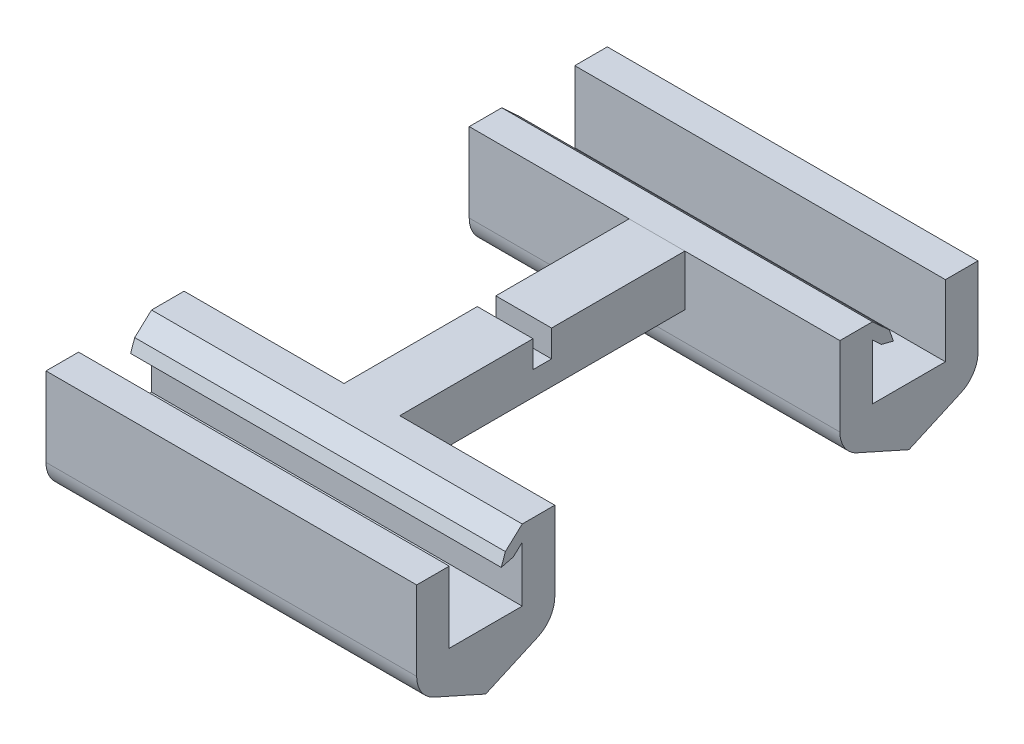
SolidWorks part; units mm, degrees
ref_plane "Front Plane" through (0, 0, 0) normal (0, 0, 1) x (1, 0, 0)
ref_plane "Top Plane" through (0, 0, 0) normal (0, 1, 0) x (1, 0, 0)
ref_plane "Right Plane" through (0, 0, 0) normal (1, 0, 0) x (0, 0, -1)
sketch "Sketch1" plane through (0, 0, 0) normal (1, 0, 0) x (0, 0, -1)
  line L0 (0, 0) -> (0, 50000) construction
  line L1 (6, -0.5435) -> (6, 0) construction
  line L2 (6.717, -0.9314) -> (6.4415, -0.6779) construction
  line L3 (6.5769, -0.5307) -> (6.3061, -0.8251) construction
  line L4 (6.3061, -0.8251) -> (6, -0.5435)
  line L5 (6.717, -0.9314) -> (6.3061, -0.8251)
  line L6 (6.5769, -0.5307) -> (6.717, -0.9314)
  line L7 (6, 0) -> (6.5769, -0.5307)
  line L8 (4.8841, 0) -> (4.8841, -2.7135)
  line L9 (5.4755, -3.6262) -> (7.25, -4.4206)
  line L10 (7.25, -1.3683) -> (7.25, 49998.6317) construction
  line L11 (-7.25, -1.3683) -> (-7.25, 49998.6317) construction
  line L12 (-6, 0) -> (-4.8841, 0)
  line L13 (-6, -2.4374) -> (-6, -0.5435)
  line L14 (-8.5, -2.4374) -> (-6, -2.4374)
  line L15 (-9.0245, -3.6262) -> (-7.25, -4.4206)
  line L16 (-9.6159, 0) -> (-9.6159, -2.7135)
  line L17 (-8.5, -2.4374) -> (-8.5, 0)
  line L18 (-8.5, 0) -> (-9.6159, 0)
  line L19 (-5.4755, -3.6262) -> (-7.25, -4.4206)
  line L20 (-4.8841, 0) -> (-4.8841, -2.7135)
  line L21 (-6, 0) -> (-6.5769, -0.5307)
  line L22 (-6.5769, -0.5307) -> (-6.717, -0.9314)
  line L23 (-6.717, -0.9314) -> (-6.3061, -0.8251)
  line L24 (-6.3061, -0.8251) -> (-6, -0.5435)
  line L25 (-6.5769, -0.5307) -> (-6.3061, -0.8251) construction
  line L26 (-6.717, -0.9314) -> (-6.4415, -0.6779) construction
  line L27 (-6, -0.5435) -> (-6, 0) construction
  line L28 (8.5, 0) -> (9.6159, 0)
  line L29 (8.5, -2.4374) -> (8.5, 0)
  line L30 (9.6159, 0) -> (9.6159, -2.7135)
  line L31 (9.0245, -3.6262) -> (7.25, -4.4206)
  line L32 (8.5, -2.4374) -> (6, -2.4374)
  line L33 (6, -2.4374) -> (6, -0.5435)
  line L34 (6, 0) -> (4.8841, 0)
  arc A0 (-5.4755, -3.6262) -> (-4.8841, -2.7135) centre (-5.8841, -2.7135) ccw
  arc A1 (-9.0245, -3.6262) -> (-9.6159, -2.7135) centre (-8.6159, -2.7135) cw
  arc A2 (9.0245, -3.6262) -> (9.6159, -2.7135) centre (8.6159, -2.7135) ccw
  arc A3 (5.4755, -3.6262) -> (4.8841, -2.7135) centre (5.8841, -2.7135) cw
  point P27 (-4.8841, -3.3614)
  point P35 (-6, -0.4524)
  point P45 (4.8841, -3.3614)
  dimension "D3" = 1
  dimension "D1" = 12
  dimension "D4" = 0.4
extrude "Boss-Extrude1" add sketch "Sketch1" along normal blind 12.7
sketch "Sketch2" plane through (0, 0, -4.8841) normal (0, 0, 1) x (1, 0, 0)
  line L1 (5.4781, 0) -> (7.3878, 0)
  line L2 (5.4781, 0) -> (5.4781, -1.7417)
  line L3 (5.4781, -1.7417) -> (7.3878, -1.7417) construction
  line L4 (7.3878, 0) -> (7.3878, -1.7417)
  line L5 (5.4781, -1.7417) -> (6.433, -2.6965)
  line L6 (6.433, -2.6965) -> (7.3878, -1.7417)
  line L7 (12.7, 0) -> (0, 0) construction
extrude "Boss-Extrude2" add sketch "Sketch2" along normal up to next
sketch "Sketch3" plane through (5.4781, 0, 0) normal (-1, 0, 0) x (0, 0, 1)
  line L0 (0, 0) -> (0, -50000) construction
  line L1 (4.8841, 0) -> (-4.8841, 0) construction
  line L2 (0.3175, -0.9172) -> (0.3175, 0)
  line L3 (-0.3175, -0.9172) -> (-0.3175, 0)
  line L4 (-0.3175, 0) -> (0.3175, 0)
  line L5 (0.3175, -0.9172) -> (-0.3175, -0.9172)
  point P4 (0, 0)
  dimension "D1" = 0.635
extrude "Cut-Extrude1" cut sketch "Sketch3" against normal up to next (1.9097 mm away)
